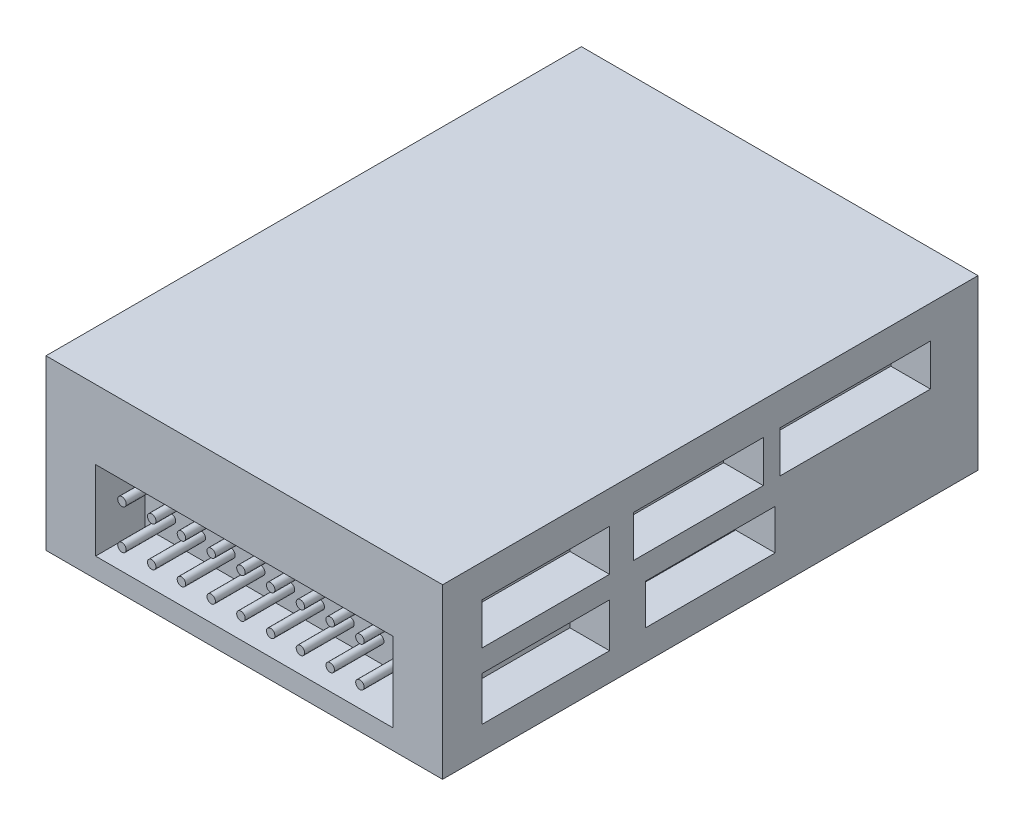
SolidWorks part; units mm, degrees
ref_plane "Front Plane" through (0, 0, 0) normal (0, 0, 1) x (1, 0, 0)
ref_plane "Top Plane" through (0, 0, 0) normal (0, 1, 0) x (1, 0, 0)
ref_plane "Right Plane" through (0, 0, 0) normal (1, 0, 0) x (0, 0, -1)
sketch "Sketch1" plane through (0, 0, 0) normal (0, 1, 0) x (1, 0, 0)
  line L1 (20, -27) -> (-20, -27)
  line L2 (20, -27) -> (20, 27)
  line L3 (20, 27) -> (-20, 27)
  line L4 (-20, -27) -> (-20, 27)
  line L5 (20, -27) -> (-20, 27) construction
  line L6 (20, 27) -> (-20, -27) construction
  point P0 (0, 0)
  dimension "D1" = 40
  dimension "D2" = 54
extrude "Boss-Extrude1" add sketch "Sketch1" along normal blind 17
sketch "Sketch2" plane through (0, 0, 27) normal (0, 0, 1) x (1, 0, 0)
  line L1 (-15, 2) -> (15, 2)
  line L2 (-15, 2) -> (-15, 10)
  line L3 (-15, 10) -> (15, 10)
  line L4 (15, 2) -> (15, 10)
  line L5 (-15, 2) -> (15, 10) construction
  line L6 (-15, 10) -> (15, 2) construction
  circle A0 centre (-12.3397, 8.0944) radius 0.4261
  circle A1 centre (-9.3397, 8.0944) radius 0.4261
  circle A2 centre (-6.3397, 8.0944) radius 0.4261
  circle A3 centre (-3.3397, 8.0944) radius 0.4261
  circle A4 centre (-0.3397, 8.0944) radius 0.4261
  circle A5 centre (2.6603, 8.0944) radius 0.4261
  circle A6 centre (5.6603, 8.0944) radius 0.4261
  circle A7 centre (8.6603, 8.0944) radius 0.4261
  circle A8 centre (11.6603, 8.0944) radius 0.4261
  circle A9 centre (-9.3397, 4.0944) radius 0.4261
  circle A10 centre (-6.3397, 4.0944) radius 0.4261
  circle A11 centre (-3.3397, 4.0944) radius 0.4261
  circle A12 centre (-0.3397, 4.0944) radius 0.4261
  circle A13 centre (2.6603, 4.0944) radius 0.4261
  circle A14 centre (5.6603, 4.0944) radius 0.4261
  circle A15 centre (8.6603, 4.0944) radius 0.4261
  circle A16 centre (11.6603, 4.0944) radius 0.4261
  circle A17 centre (-12.3397, 4.0944) radius 0.4261
  point P0 (0, 6)
  dimension "D1" = 8
  dimension "D2" = 30
  dimension "D3" = 6
  dimension "D4" = 0
  dimension "D5" = 9
  dimension "D6" = 2
extrude "Cut-Extrude1" cut sketch "Sketch2" against normal blind 5
sketch "Sketch3" plane through (20, 0, 0) normal (1, 0, 0) x (0, 0, -1)
  line L1 (-23.0101, 9.4884) -> (-10.1615, 9.4884)
  line L2 (-23.0101, 9.4884) -> (-23.0101, 13.6889)
  line L3 (-23.0101, 13.6889) -> (-10.1615, 13.6889)
  line L4 (-10.1615, 9.4884) -> (-10.1615, 13.6889)
  line L5 (-23.0101, 9.4884) -> (-10.1615, 13.6889) construction
  line L6 (-23.0101, 13.6889) -> (-10.1615, 9.4884) construction
  line L7 (-7.7524, 9.4884) -> (5.3433, 9.4884)
  line L8 (-7.7524, 9.4884) -> (-7.7524, 13.6889)
  line L9 (-7.7524, 13.6889) -> (5.3433, 13.6889)
  line L10 (5.3433, 9.4884) -> (5.3433, 13.6889)
  line L11 (-7.7524, 9.4884) -> (5.3433, 13.6889) construction
  line L12 (-7.7524, 13.6889) -> (5.3433, 9.4884) construction
  line L13 (7.0111, 9.4884) -> (22.2071, 9.4884)
  line L14 (7.0111, 9.4884) -> (7.0111, 13.6889)
  line L15 (7.0111, 13.6889) -> (22.2071, 13.6889)
  line L16 (22.2071, 9.4884) -> (22.2071, 13.6889)
  line L17 (7.0111, 9.4884) -> (22.2071, 13.6889) construction
  line L18 (7.0111, 13.6889) -> (22.2071, 9.4884) construction
  line L19 (-23.0101, 2.817) -> (-10.1615, 2.817)
  line L20 (-23.0101, 2.817) -> (-23.0101, 7.2646)
  line L21 (-23.0101, 7.2646) -> (-10.1615, 7.2646)
  line L22 (-10.1615, 2.817) -> (-10.1615, 7.2646)
  line L23 (-23.0101, 2.817) -> (-10.1615, 7.2646) construction
  line L24 (-23.0101, 7.2646) -> (-10.1615, 2.817) construction
  line L25 (-6.5478, 3.0023) -> (6.5478, 3.0023)
  line L26 (-6.5478, 3.0023) -> (-6.5478, 7.0792)
  line L27 (-6.5478, 7.0792) -> (6.5478, 7.0792)
  line L28 (6.5478, 3.0023) -> (6.5478, 7.0792)
  line L29 (-6.5478, 3.0023) -> (6.5478, 7.0792) construction
  line L30 (-6.5478, 7.0792) -> (6.5478, 3.0023) construction
  point P0 (-16.5858, 11.5886)
  point P5 (-1.2046, 11.5886)
  point P10 (14.6091, 11.5886)
  point P15 (-16.5858, 5.0408)
  point P20 (0, 5.0408)
extrude "Cut-Extrude2" cut sketch "Sketch3" against normal blind 4
